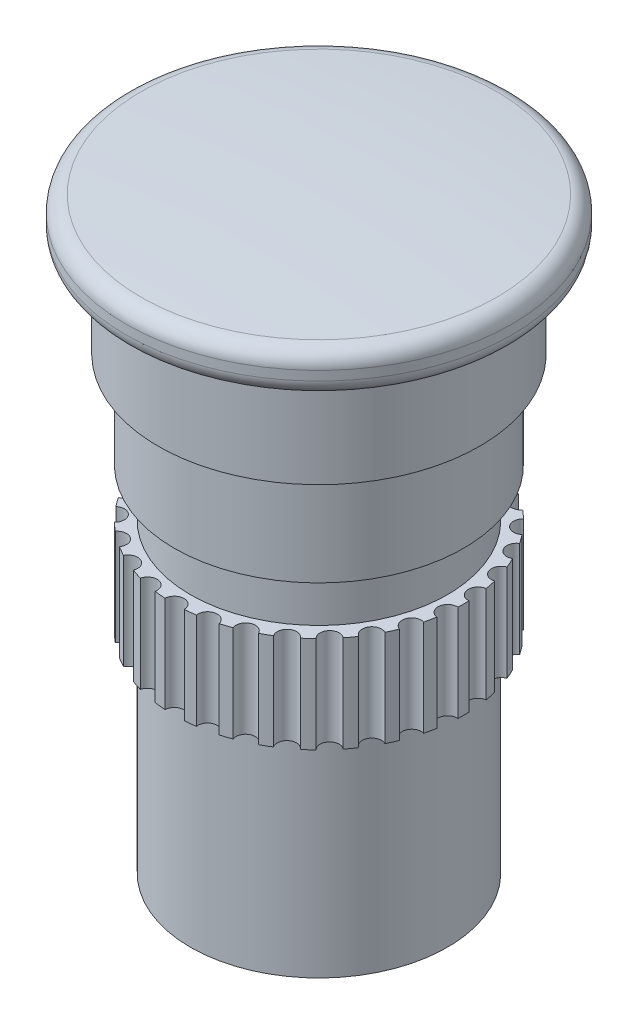
SolidWorks part; units mm, degrees
ref_plane "前视基准面" through (0, 0, 0) normal (0, 0, 1) x (1, 0, 0)
ref_plane "上视基准面" through (0, 0, 0) normal (0, 1, 0) x (1, 0, 0)
ref_plane "右视基准面" through (0, 0, 0) normal (1, 0, 0) x (0, 0, -1)
sketch "草图1" plane through (0, 0, 0) normal (0, 0, 1) x (1, 0, 0)
  line L0 (12, 2.5) -> (12, 0)
  line L5 (0, 0) -> (12, 0)
  line L7 (0, 12.796) -> (0, -141.25) construction
  line L8 (0, 3) -> (0, 0)
  arc A2 (12, 2.5) -> (0, 3) centre (0, -141.25) ccw
  dimension "D1" = 12
  dimension "D2" = 2.5
  dimension "D3" = 3
revolve "旋转1" add sketch "草图1" angle 360 about L8
sketch "草图3" plane through (0, 0, 0) normal (0, -1, 0) x (1, 0, 0)
  circle A0 centre (0, 0) radius 10
  dimension "D1" = 20
extrude "凸台-拉伸1" add sketch "草图3" along normal blind 6
sketch "草图5" plane through (0, -6, 0) normal (0, -1, 0) x (1, 0, 0)
  circle A0 centre (0, 0) radius 9
  dimension "D1" = 18
extrude "凸台-拉伸2" add sketch "草图5" along normal blind 6
sketch "草图7" plane through (0, -12, 0) normal (0, -1, 0) x (1, 0, 0)
  circle A0 centre (0, 0) radius 8
  circle A1 centre (0, 0) radius 9 construction
  dimension "D1" = 16
extrude "凸台-拉伸3" add sketch "草图7" along normal blind 3
sketch "草图10" plane through (0, -15, 0) normal (0, -1, 0) x (1, 0, 0)
  circle A0 centre (0, 0) radius 9
  dimension "D1" = 18
extrude "凸台-拉伸4" add sketch "草图10" along normal blind 6
sketch "草图11" plane through (0, -21, 0) normal (0, -1, 0) x (1, 0, 0)
  circle A0 centre (0, 0) radius 8
  dimension "D1" = 16
extrude "凸台-拉伸5" add sketch "草图11" along normal blind 13
fillet "圆角1" radius 1 2 edges at (-12, 2.5, 0) (-12, 0, 0)
sketch "草图12" plane through (0, -21, 0) normal (0, -1, 0) x (1, 0, 0)
  circle A0 centre (0, 9) radius 0.6
  circle A1 centre (0, 0) radius 9 construction
  circle A2 centre (0, 0) radius 9 construction
  circle A3 centre (1.8712, 8.8033) radius 0.6
  circle A4 centre (3.6606, 8.2219) radius 0.6
  circle A5 centre (5.2901, 7.2812) radius 0.6
  circle A6 centre (6.6883, 6.0222) radius 0.6
  circle A7 centre (7.7942, 4.5) radius 0.6
  circle A8 centre (8.5595, 2.7812) radius 0.6
  circle A9 centre (8.9507, 0.9408) radius 0.6
  circle A10 centre (8.9507, -0.9408) radius 0.6
  circle A11 centre (8.5595, -2.7812) radius 0.6
  circle A12 centre (7.7942, -4.5) radius 0.6
  circle A13 centre (6.6883, -6.0222) radius 0.6
  circle A14 centre (5.2901, -7.2812) radius 0.6
  circle A15 centre (3.6606, -8.2219) radius 0.6
  circle A16 centre (1.8712, -8.8033) radius 0.6
  circle A17 centre (0, -9) radius 0.6
  circle A18 centre (-1.8712, -8.8033) radius 0.6
  circle A19 centre (-3.6606, -8.2219) radius 0.6
  circle A20 centre (-5.2901, -7.2812) radius 0.6
  circle A21 centre (-6.6883, -6.0222) radius 0.6
  circle A22 centre (-7.7942, -4.5) radius 0.6
  circle A23 centre (-8.5595, -2.7812) radius 0.6
  circle A24 centre (-8.9507, -0.9408) radius 0.6
  circle A25 centre (-8.9507, 0.9408) radius 0.6
  circle A26 centre (-8.5595, 2.7812) radius 0.6
  circle A27 centre (-7.7942, 4.5) radius 0.6
  circle A28 centre (-6.6883, 6.0222) radius 0.6
  circle A29 centre (-5.2901, 7.2812) radius 0.6
  circle A30 centre (-3.6606, 8.2219) radius 0.6
  circle A31 centre (-1.8712, 8.8033) radius 0.6
  point P68 (0, 0)
  dimension "D1" = 1.2
  dimension "D2" = 30
extrude "切除-拉伸1" cut sketch "草图12" against normal blind 6
